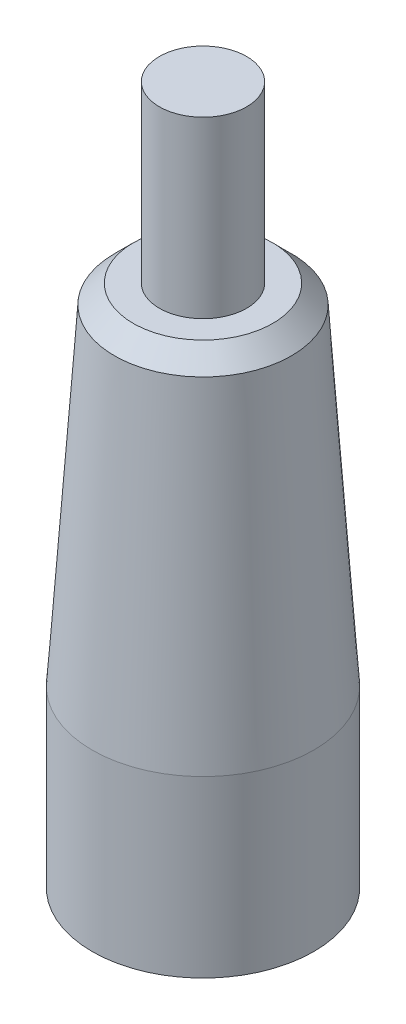
SolidWorks part; units mm, degrees
ref_plane "Front" through (0, 0, 0) normal (0, 0, 1) x (1, 0, 0)
ref_plane "Top" through (0, 0, 0) normal (0, 1, 0) x (1, 0, 0)
ref_plane "Right" through (0, 0, 0) normal (1, 0, 0) x (0, 0, -1)
sketch "Sketch4" plane through (0, 0, 0) normal (0, 0, 1) x (1, 0, 0)
  line L0 (0, 0) -> (0, 15)
  line L1 (0, 15) -> (2.5, 15) construction
  line L5 (3.175, 5) -> (3.175, 0)
  line L6 (3.175, 0) -> (0, 0)
  line L7 (2.5, 15) -> (3.175, 5)
  line L8 (0, 15) -> (0, 20)
  line L9 (0, 20) -> (1.25, 20)
  line L10 (1.25, 20) -> (1.25, 15)
  line L11 (1.25, 15) -> (2.5, 15)
  dimension "D1" = 15
  dimension "D2" = 2.5
  dimension "D3" = 5
  dimension "D4" = 5
  dimension "D5" = 1.25
  dimension "D6" = 3.175
revolve "Revolve1" add sketch "Sketch4" angle 360 about L0
sketch "Sketch6" plane through (0, 15, 0) normal (0, 1, 0) x (1, 0, 0)
  circle A0 centre (0, 0) radius 2
  circle A1 centre (0, 0) radius 3
  dimension "D1" = 4
  dimension "D2" = 6
extrude "Cut-Extrude1" [suppressed] cut sketch "Sketch6" against normal blind 1
chamfer "Chamfer3" distance 0.5 angle 45 1 edges at (2.5, 15, 0)
